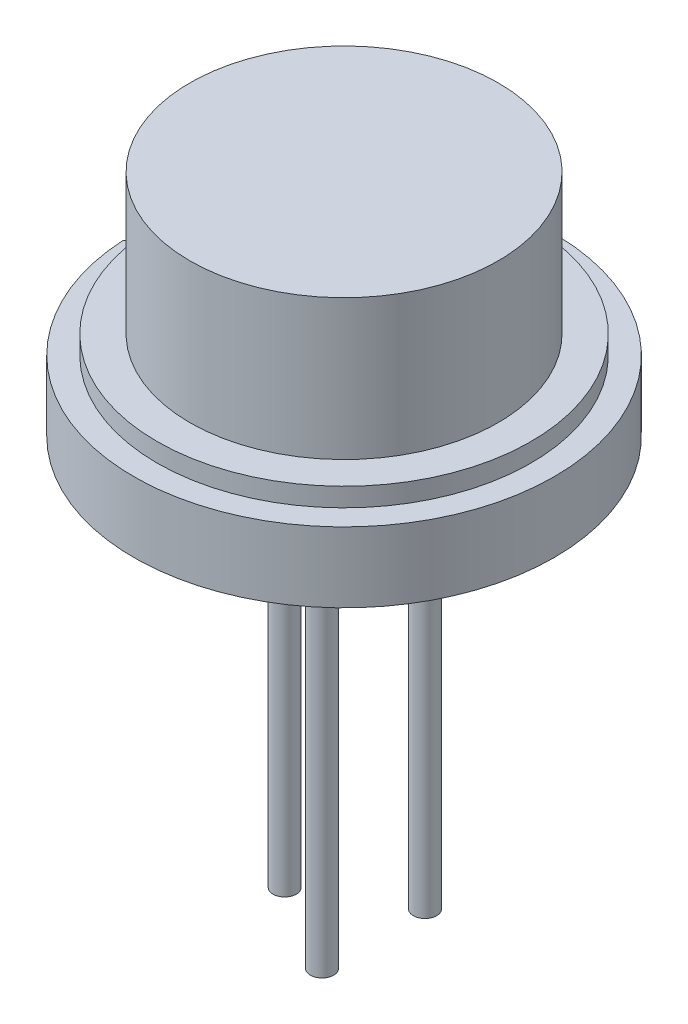
SolidWorks part; units mm, degrees
ref_plane "Спереди" through (0, 0, 0) normal (0, 0, 1) x (1, 0, 0)
ref_plane "Сверху" through (0, 0, 0) normal (0, 1, 0) x (1, 0, 0)
ref_plane "Справа" through (0, 0, 0) normal (1, 0, 0) x (0, 0, -1)
sketch "Эскиз2" plane through (0, 0, 0) normal (0, 1, 0) x (1, 0, 0)
  circle A1 centre (-1.27, 0) radius 0.25
  circle A2 centre (0.631, 1.1022) radius 0.25
  circle A3 centre (0.631, -1.1022) radius 0.25
  point P2 (0.631, 1.1022)
  point P9 (0.631, -1.1022)
extrude "Бобышка-Вытянуть1" add sketch "Эскиз2" along normal blind 9
sketch "Эскиз3" plane through (0, 9, 0) normal (0, 1, 0) x (1, 0, 0)
  line L1 (-4.2473, 0) -> (-4.4933, 0.2459)
  line L2 (-4.2473, 0) -> (-4.4933, -0.2459)
  arc A0 (-4.4933, -0.2459) -> (-4.4933, 0.2459) centre (0, 0) ccw
extrude "Бобышка-Вытянуть2" add sketch "Эскиз3" along normal blind 1.5
sketch "Эскиз4" plane through (0, 10.5, 0) normal (0, 1, 0) x (1, 0, 0)
  line L4 (-4.25, 0) -> (-4.4934, -0.2434)
  line L5 (-4.25, 0) -> (-4.4934, 0.2434)
  line L6 (-4.4934, 0.2434) -> (-4.4934, -0.2434)
  circle A0 centre (0, 0) radius 4
  circle A2 centre (0, 0) radius 4.5
extrude "Бобышка-Вытянуть3" add sketch "Эскиз4" along normal blind 0.4 contours A0
sketch "Эскиз5" plane through (0, 10.9, 0) normal (0, 1, 0) x (1, 0, 0)
  circle A0 centre (0, 0) radius 3.3
extrude "Бобышка-Вытянуть4" add sketch "Эскиз5" along normal blind 3
